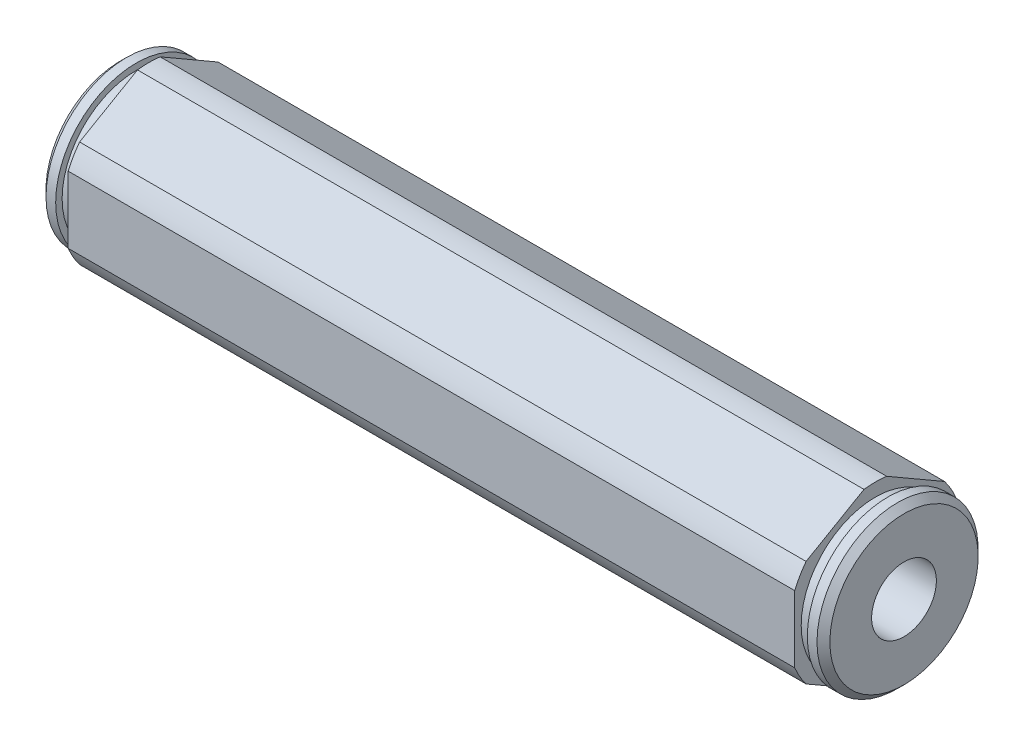
SolidWorks part; units mm, degrees
material "6061-T6 (SS)"
ref_plane "Front Plane" through (0, 0, 0) normal (0, 0, 1) x (1, 0, 0)
ref_plane "Top Plane" through (0, 0, 0) normal (0, 1, 0) x (1, 0, 0)
ref_plane "Right Plane" through (0, 0, 0) normal (1, 0, 0) x (0, 0, -1)
sketch "Sketch1" plane through (0, 0, 0) normal (1, 0, 0) x (0, 0, -1)
  line L1 (0.893, -6.8168) -> (5.457, -4.1818)
  line L2 (6.35, -2.635) -> (6.35, 2.635)
  line L3 (5.457, 4.1818) -> (0.893, 6.8168)
  line L4 (-0.893, 6.8168) -> (-5.457, 4.1818)
  line L5 (-6.35, 2.635) -> (-6.35, -2.635)
  line L6 (-5.457, -4.1818) -> (-0.893, -6.8168)
  circle A0 centre (0, 0) radius 6.35 construction
  arc A1 (6.35, 2.635) -> (5.457, 4.1818) centre (0, 0) ccw
  arc A2 (0.893, 6.8168) -> (-0.893, 6.8168) centre (0, 0) ccw
  arc A3 (-5.457, 4.1818) -> (-6.35, 2.635) centre (0, 0) ccw
  arc A4 (-6.35, -2.635) -> (-5.457, -4.1818) centre (0, 0) ccw
  arc A5 (-0.893, -6.8168) -> (0.893, -6.8168) centre (0, 0) ccw
  arc A6 (5.457, -4.1818) -> (6.35, -2.635) centre (0, 0) ccw
  circle A7 centre (0, 0) radius 2.54
  dimension "D1" = 12.7
  dimension "D2" = 13.75
  dimension "D3" = 5.08
sketch "Sketch2" plane through (0, 0, 0) normal (1, 0, 0) x (0, 0, -1)
  line L1 (5.457, 4.1818) -> (0.893, 6.8168)
  line L2 (-0.893, 6.8168) -> (-5.457, 4.1818)
  line L3 (-6.35, 2.635) -> (-6.35, -2.635)
  line L4 (-5.457, -4.1818) -> (-0.893, -6.8168)
  line L5 (0.893, -6.8168) -> (5.457, -4.1818)
  line L6 (6.35, -2.635) -> (6.35, 2.635)
  circle A0 centre (0, 0) radius 6.35 construction
  arc A1 (5.457, -4.1818) -> (6.35, -2.635) centre (0, 0) ccw
  arc A2 (6.35, 2.635) -> (5.457, 4.1818) centre (0, 0) ccw
  arc A3 (0.893, 6.8168) -> (-0.893, 6.8168) centre (0, 0) ccw
  arc A4 (-5.457, 4.1818) -> (-6.35, 2.635) centre (0, 0) ccw
  arc A5 (-6.35, -2.635) -> (-5.457, -4.1818) centre (0, 0) ccw
  arc A6 (-0.893, -6.8168) -> (0.893, -6.8168) centre (0, 0) ccw
  dimension "D1" = 12.7
  dimension "D2" = 13.75
sketch "Sketch4" plane through (0, 0, 0) normal (0, 1, 0) x (1, 0, 0)
  line L0 (1.27, 6.35) -> (1.27, 5.842)
  line L1 (0, 0) -> (61.7728, 0)
  line L2 (0, 0) -> (0, 6.35)
  line L3 (0, 6.35) -> (1.27, 6.35)
  line L4 (61.7728, 0) -> (61.7728, 6.35)
  line L5 (1.27, 5.842) -> (2.2606, 5.842)
  line L6 (2.2606, 5.842) -> (2.2606, 7.62)
  line L7 (2.2606, 7.62) -> (59.5122, 7.62)
  line L8 (60.5028, 6.35) -> (61.7728, 6.35)
  line L10 (60.5028, 6.35) -> (60.5028, 5.842)
  line L11 (60.5028, 5.842) -> (59.5122, 5.842)
  line L13 (59.5122, 5.842) -> (59.5122, 7.62)
  dimension "D1" = 7.62
  dimension "D2" = 57.2516
  dimension "D3" = 5.842
  dimension "D4" = 0.9906
  dimension "D5" = 1.27
  dimension "D7" = 0.9906
  dimension "D8" = 1.27
  dimension "D9" = 6.35
  dimension "D10" = 6.35
revolve "Revolve1" add sketch "Sketch4" angle 360 about L1
extrude "Cut-Extrude1" cut sketch "Sketch2" along normal up to next flip side to cut
sketch "Sketch5" plane through (61.7728, 0, 0) normal (1, 0, 0) x (0, 0, -1)
  circle A0 centre (0, 0) radius 2.5527
  dimension "D1" = 5.1054
extrude "Cut-Extrude2" cut sketch "Sketch5" against normal up to surface (61.7728 mm away) up to face at (0, 0, 6.35)
chamfer "Chamfer1" distance 0.508 angle 45 2 edges at (0, 0, 6.35) (61.7728, 0, 6.35)
